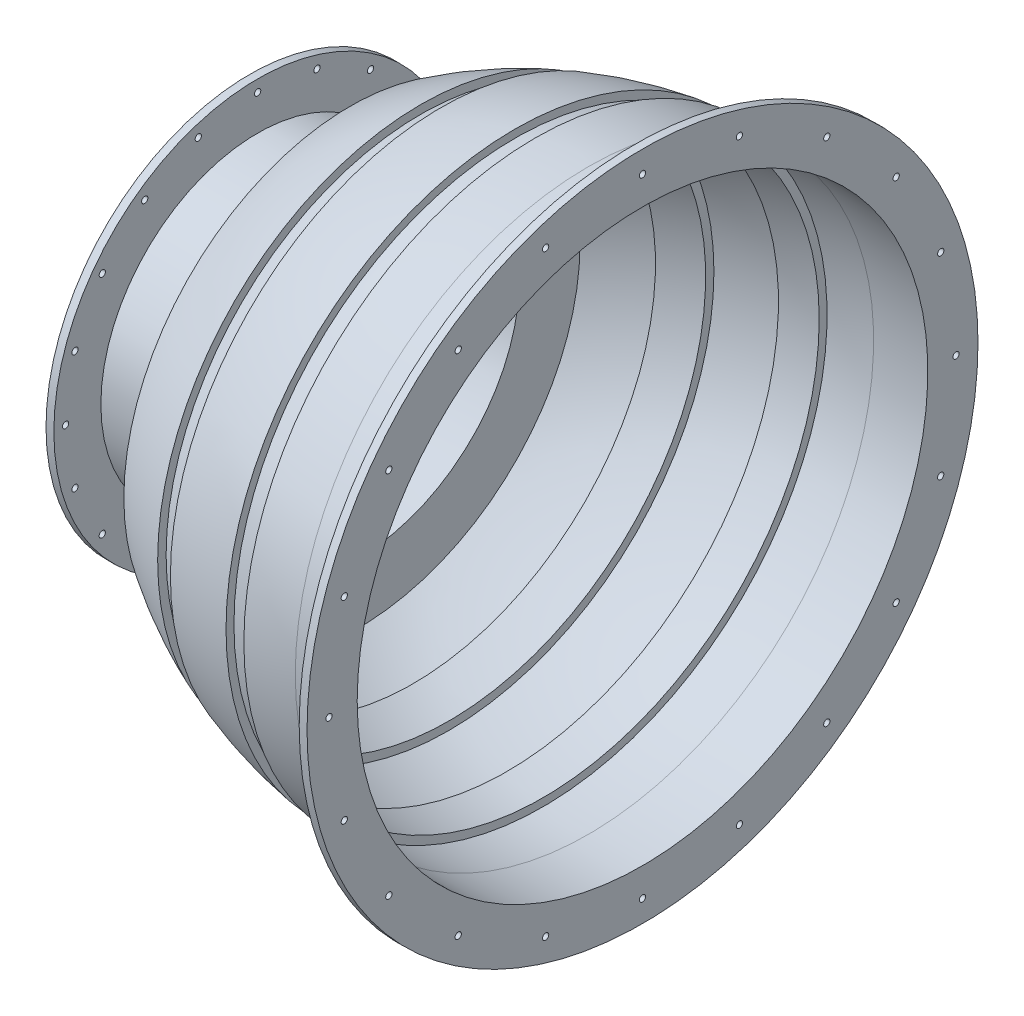
SolidWorks part; units mm, degrees
ref_plane "Front Plane" through (0, 0, 0) normal (0, 0, 1) x (1, 0, 0)
ref_plane "Top Plane" through (0, 0, 0) normal (0, 1, 0) x (1, 0, 0)
ref_plane "Right Plane" through (0, 0, 0) normal (1, 0, 0) x (0, 0, -1)
sketch "Sketch1" plane through (0, 0, 0) normal (0, 0, 1) x (1, 0, 0)
  line L0 (-99.3491, 0) -> (125.4121, 0) construction
  line L1 (125.35, 214) -> (125.35, 182)
  line L2 (125.35, 182) -> (90.7774, 182)
  line L3 (-56.15, 141.6187) -> (-56.15, 103)
  line L4 (-56.15, 103) -> (-85.15, 95)
  line L5 (-85.15, 95) -> (-125.15, 95)
  line L6 (-125.15, 95) -> (-125.15, 130)
  line L7 (1.85, 185.9148) -> (1.85, 0) construction
  line L8 (-21.15, 185.9148) -> (-21.15, 0) construction
  line L9 (38.85, 178.3016) -> (38.85, 0) construction
  line L10 (61.85, 181.4796) -> (61.85, 0) construction
  line L11 (120.35, 214) -> (120.35, 187)
  line L12 (120.35, 187) -> (90.85, 187)
  line L13 (-61.15, 144.35) -> (-61.15, 106.8075)
  line L14 (-61.15, 106.8075) -> (-85.827, 100)
  line L15 (-85.827, 100) -> (-120.15, 100)
  line L16 (-120.15, 100) -> (-120.15, 130)
  line L17 (43.85, 184.174) -> (43.85, 179.1169)
  line L18 (56.85, 185.7982) -> (56.85, 180.7728)
  line L19 (-16.15, 167.7855) -> (-16.15, 162.3837)
  line L20 (-3.15, 172.6501) -> (-3.15, 167.3555)
  line L23 (-125.15, 130) -> (-120.15, 130)
  line L24 (120.35, 214) -> (125.35, 214)
  line L25 (-21.15, 154.7858) -> (-21.15, 160.255)
  line L26 (1.85, 169.0589) -> (1.85, 163.7891)
  line L27 (38.85, 178.3016) -> (38.85, 173.2257)
  line L28 (61.85, 181.2332) -> (61.85, 176.216)
  line L30 (-130.15, 90) -> (-130.15, 130) construction
  line L31 (-84.473, 90) -> (-130.15, 90) construction
  line L32 (-51.15, 99.1925) -> (-84.473, 90) construction
  line L33 (-51.15, 138.8529) -> (-51.15, 99.1925) construction
  line L34 (130.35, 214) -> (130.35, 177) construction
  line L35 (130.35, 177) -> (90.7041, 177) construction
  arc A0 (90.7774, 182) -> (61.85, 181.2332) centre (83.1922, -77.8893) ccw
  arc A1 (90.85, 187) -> (56.85, 185.7982) centre (83.1922, -77.8893) ccw
  arc A2 (61.85, 176.216) -> (38.85, 173.2257) centre (83.1922, -77.8893) ccw
  arc A3 (90.7041, 177) -> (-51.15, 138.8529) centre (83.1922, -77.8893) ccw construction
  arc A4 (1.85, 163.7891) -> (-21.15, 154.7858) centre (83.1922, -77.8893) ccw
  arc A5 (-16.15, 167.7855) -> (-61.15, 144.35) centre (83.1922, -77.8893) ccw
  arc A6 (90.85, 187) -> (-61.15, 144.35) centre (83.1922, -77.8893) ccw construction
  arc A7 (-21.15, 160.255) -> (-56.15, 141.6187) centre (83.1922, -77.8893) ccw
  arc A8 (90.7774, 182) -> (-56.15, 141.6187) centre (83.1922, -77.8893) ccw construction
  arc A9 (-3.15, 167.3555) -> (-16.15, 162.3837) centre (83.1922, -77.8893) ccw
  arc A10 (43.85, 184.174) -> (-3.15, 172.6501) centre (83.1922, -77.8893) ccw
  arc A11 (38.85, 178.3016) -> (1.85, 169.0589) centre (83.1922, -77.8893) ccw
  arc A12 (56.85, 180.7728) -> (43.85, 179.1169) centre (83.1922, -77.8893) ccw
  dimension "D1" = 260
  dimension "D2" = 250.5
  dimension "D3" = 125.15
  dimension "D4" = 40
  dimension "D5" = 69
  dimension "D8" = 37
  dimension "D9" = 23
  dimension "D10" = 5
  dimension "D11" = 5
  dimension "D12" = 5
  dimension "D13" = 5
  dimension "D14" = 23
  dimension "D15" = 34
  dimension "D16" = 40
  dimension "D17" = 182
  dimension "D18" = 214
  dimension "D19" = 103
  dimension "D20" = 95
  dimension "D21" = 130
  dimension "D6" = 5
  dimension "D7" = 5
revolve "Revolve1" add sketch "Sketch1" angle 360 about L0
sketch "Sketch2" plane through (-125.15, 0, 0) normal (-1, 0, 0) x (0, 0, 1)
  circle A0 centre (0, 122.5) radius 2
  circle A1 centre (0, 0) radius 144.35 construction
  dimension "D1" = 122.5
  dimension "D2" = 4
extrude "Cut-Extrude1" cut sketch "Sketch2" against normal blind 10
sketch "Sketch3" plane through (125.35, 0, 0) normal (1, 0, 0) x (0, 0, -1)
  circle A0 centre (0, 200) radius 2
  dimension "D2" = 4
  dimension "D1" = 200
extrude "Cut-Extrude2" cut sketch "Sketch3" against normal blind 10
pattern_circular "CirPattern1" count 20 over 360 about axis through (0, 0, 0) along (1, 0, 0) of "Cut-Extrude2", "Cut-Extrude1"
